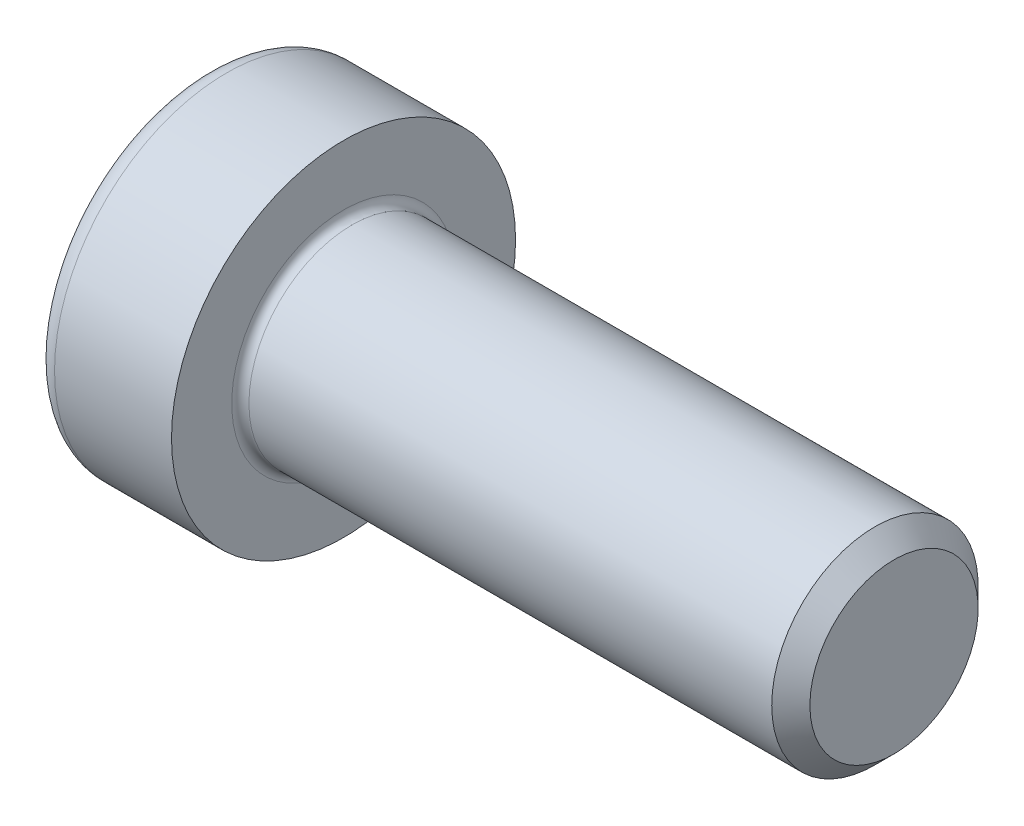
SolidWorks part; units mm, degrees
revolve "Base-Revolve" add sketch "BodySke"
sketch "BodySke" plane through (0, 0, 0) normal (0, 0, 1) x (1, 0, 0)
  line L0 (0, 0) -> (0, 5)
  line L1 (0, 5) -> (4, 5)
  line L2 (4, 5) -> (4, 3)
  line L3 (4, 3) -> (19.4455, 3)
  line L4 (20, 2.4455) -> (20, 0)
  line L5 (20, 0) -> (0, 0)
  line L6 (-31.75, 0) -> (127, 0) construction
  line L8 (20, 2.4455) -> (19.4455, 3)
  line L10 (20, -2.4455) -> (19.4455, -3) construction
  line L11 (5, 4.525) -> (5, -1.825) construction
  line L12 (4, 4.525) -> (4, -1.825) construction
  line L13 (-40, 4.525) -> (-40, -1.825) construction
  dimension "Head_ht" = 4
  dimension "Length" = 16
  dimension "Body_ch_ang" = 45
  dimension "Diameter" = 6
  dimension "Minor_dia" = 4.891
  dimension "Advance" = 1
  dimension "Thread_nom" = 16
  dimension "Thread_length" = 60
  dimension "Head_dia" = 10
cosmetic thread "ThreadCosmetic"
fillet "Fillet1" radius 0.25 1 edges at (4, 0, 3)
fillet "Fillet2" radius 0.6 1 edges at (0, 0, 5)
ref_plane "Plane1" through (0, 0, 0) normal (0, 0, 1) x (1, 0, 0)
ref_plane "Plane2" through (0, 0, 0) normal (0, 1, 0) x (1, 0, 0)
ref_plane "Plane3" through (0, 0, 0) normal (1, 0, 0) x (0, 0, -1)
sketch "HexSke" plane through (0, 0, 0) normal (-1, 0, 0) x (0, 0.5, 0.866)
  line L0 (1.4434, 2.5) -> (-1.4434, 2.5)
  line L1 (-1.4434, 2.5) -> (-2.8868, 0)
  line L2 (1.4434, 2.5) -> (2.8868, 0)
  line L3 (1.4434, -2.5) -> (2.8868, 0)
  line L4 (1.4434, -2.5) -> (-1.4434, -2.5)
  line L5 (-1.4434, -2.5) -> (-2.8868, 0)
  dimension "D1" = 2.5
  dimension "D2" = 2.5
  dimension "Hex_size" = 5
extrude "Hex" cut sketch "HexSke" against normal blind 2.5
sketch "PilotSke" plane through (0, 0, 0) normal (0, 0, 1) x (1, 0, 0)
  line L0 (0, 2.5) -> (2.5, 2.5)
  line L1 (2.5, 2.5) -> (3.0774, 1.5)
  line L2 (-31.75, 0) -> (127, 0) construction
  line L3 (5.866, 0) -> (0, 0)
  line L4 (0, 0) -> (0, 2.5)
  line L5 (3.0774, 1.5) -> (5, 1.5)
  line L6 (0, 0) -> (47.625, 0) construction
  line L7 (5, 1.5) -> (5.866, 0)
  dimension "D1" = 2.5
  dimension "D2" = 60
  dimension "Depth" = 2.5
  dimension "Pilot_dia" = 3
  dimension "Pilot_Depth" = 5
revolve "Hex-PreBroach" cut sketch "PilotSke" angle 360 about L6
sketch "ThdSchSke" plane through (0, 0, 0) normal (0, 0, 1) x (1, 0, 0)
  line L0 (7, -2.4455) -> (6.6117, -3)
  line L1 (7, -2.4455) -> (7.3883, -3)
  line L2 (7.3883, -3) -> (7.3883, -3.75)
  line L3 (-3.175, 0) -> (5.1513, 0) construction
  line L4 (0, 4.4) -> (0, -4.4) construction
  line L5 (7.3883, -3.75) -> (6.6117, -3.75)
  line L6 (6.6117, -3.75) -> (6.6117, -3)
  dimension "Thread_minor" = 4.891
  dimension "Diameter" = 6
  dimension "Start" = 7
revolve "ThreadSchematic" [suppressed] cut sketch "ThdSchSke" angle 360 about L3
pattern_linear "ThdSchPat" [suppressed]
equation "\"D2@HexSke\" = \"Hex_size@HexSke\" / 2"
equation "\"D1@HexSke\" = \"Hex_size@HexSke\" / 2"
equation "\"D1@PilotSke\" = \"Hex_size@HexSke\" / 2"
equation "\"Thread_minor@ThreadCosmetic\"  =  \"Minor_dia@BodySke\""
equation "\"Depth@PilotSke\" =  \"Key_eng@Hex\""
equation "\"Thread_length@ThreadCosmetic\" = ((sgn( (\"Length@BodySke\" - \"Advance@BodySke\" * 3.0) - \"Thread_nom@BodySke\" )-1)*( (\"Length@BodySke\" - \"Advance@BodySke\" * 3.0) - \"Thread_nom@BodySke\" ))/-2+ \"Thread_nom@BodySke\""
equation "\"Thread_minor@ThdSchSke\" = \"Minor_dia@BodySke\""
equation "\"Diameter@ThdSchSke\" = \"Diameter@BodySke\""
equation "\"Overcut@ThdSchSke\" = \"Diameter@BodySke\" * 1.25"
equation "\"Start@ThdSchSke\" = \"Head_ht@BodySke\" + \"Length@BodySke\" - \"Thread_length@ThreadCosmetic\"  '---Non-countersunk---"
equation "\"Num_threads@ThdSchPat\" = int( \"Thread_length@ThreadCosmetic\" / \"Advance@BodySke\" + 0.999 )  + 1"
equation "\"Advance@ThdSchPat\" = \"Thread_length@ThreadCosmetic\" /  (\"Num_threads@ThdSchPat\" - 1) 'relax it"
equation "\"Num_threads@ThdSchPat\" = \"Num_threads@ThdSchPat\" - sgn( \"Num_threads@ThdSchPat\" - 1) '---chamfered tips only---"
